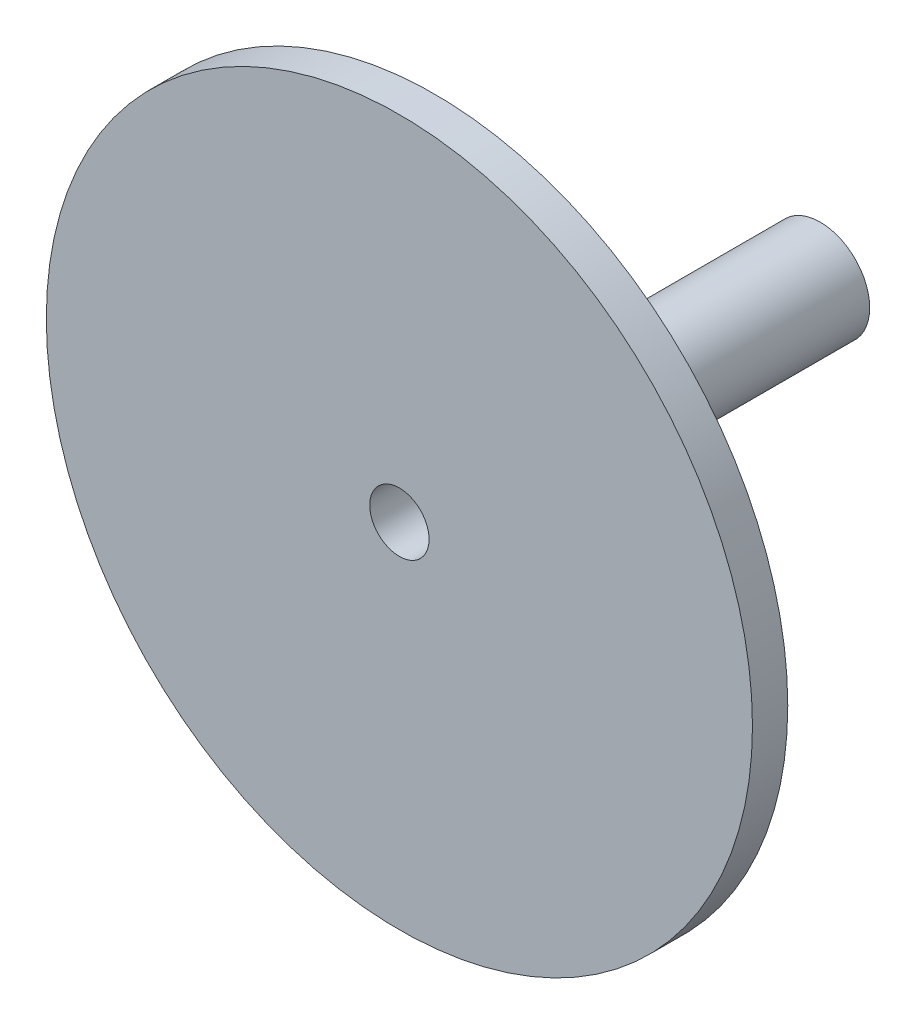
SolidWorks part; units mm, degrees
ref_plane "Front Plane" through (0, 0, 0) normal (0, 0, 1) x (1, 0, 0)
ref_plane "Top Plane" through (0, 0, 0) normal (0, 1, 0) x (1, 0, 0)
ref_plane "Right Plane" through (0, 0, 0) normal (1, 0, 0) x (0, 0, -1)
sketch "Sketch1" plane through (0, 0, 0) normal (0, 0, 1) x (1, 0, 0)
  circle A0 centre (0, 0) radius 4.445
  circle A1 centre (0, 0) radius 2.667
  dimension "D1" = 8.89
  dimension "D2" = 5.334
extrude "Boss-Extrude1" add sketch "Sketch1" along normal blind 37.846
sketch "Sketch2" plane through (0, 0, 37.846) normal (0, 0, 1) x (1, 0, 0)
  circle A0 centre (0, 0) radius 31.75
  circle A1 centre (0, 0) radius 2.667
  dimension "D1" = 5.334
  dimension "D2" = 63.5
extrude "Boss-Extrude2" add sketch "Sketch2" against normal blind 3.175 contours A0 | A1
